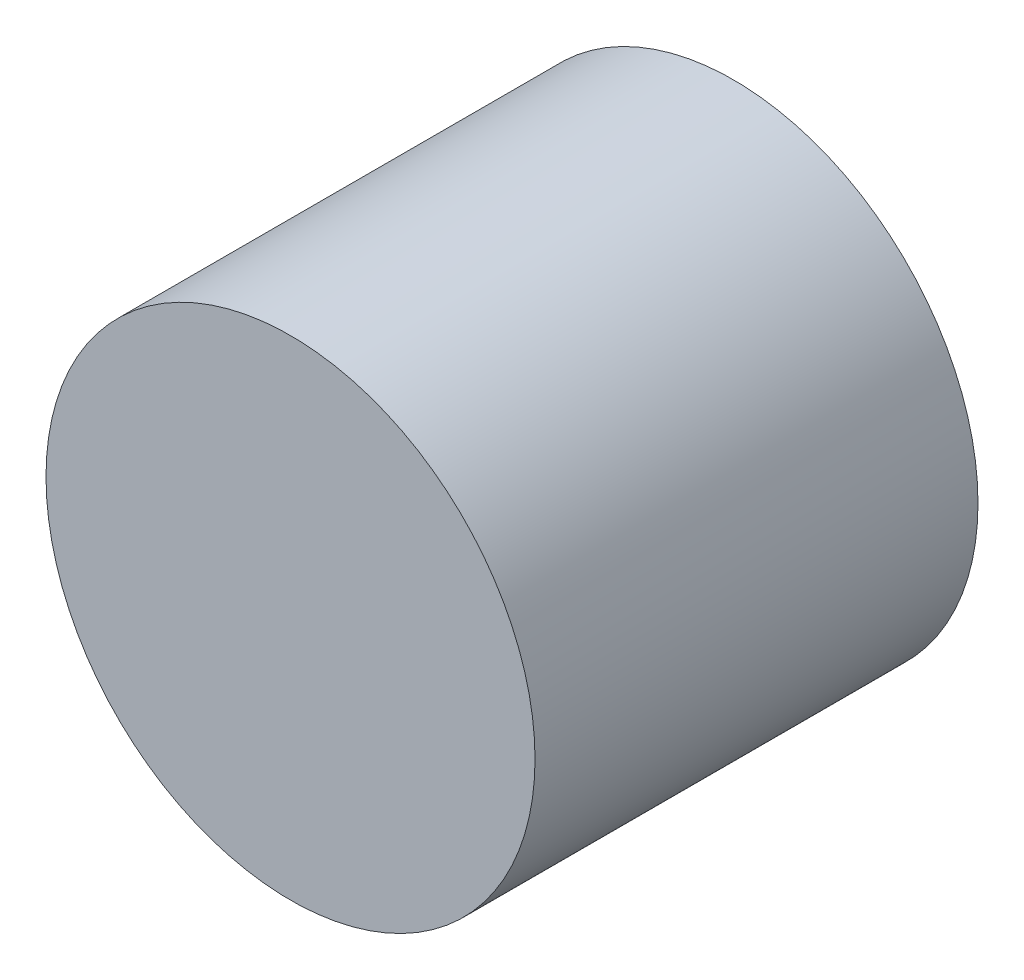
SolidWorks part; units mm, degrees
material "201 Annealed Stainless Steel (SS)"
ref_plane "Front Plane" through (0, 0, 0) normal (0, 0, 1) x (1, 0, 0)
ref_plane "Top Plane" through (0, 0, 0) normal (0, 1, 0) x (1, 0, 0)
ref_plane "Right Plane" through (0, 0, 0) normal (1, 0, 0) x (0, 0, -1)
sketch "Sketch1" plane through (0, 0, 0) normal (0, 0, 1) x (1, 0, 0)
  circle A0 centre (0, 0) radius 13.8
  dimension "D1" = 27.6
extrude "Boss-Extrude1" add sketch "Sketch1" along normal blind 25
